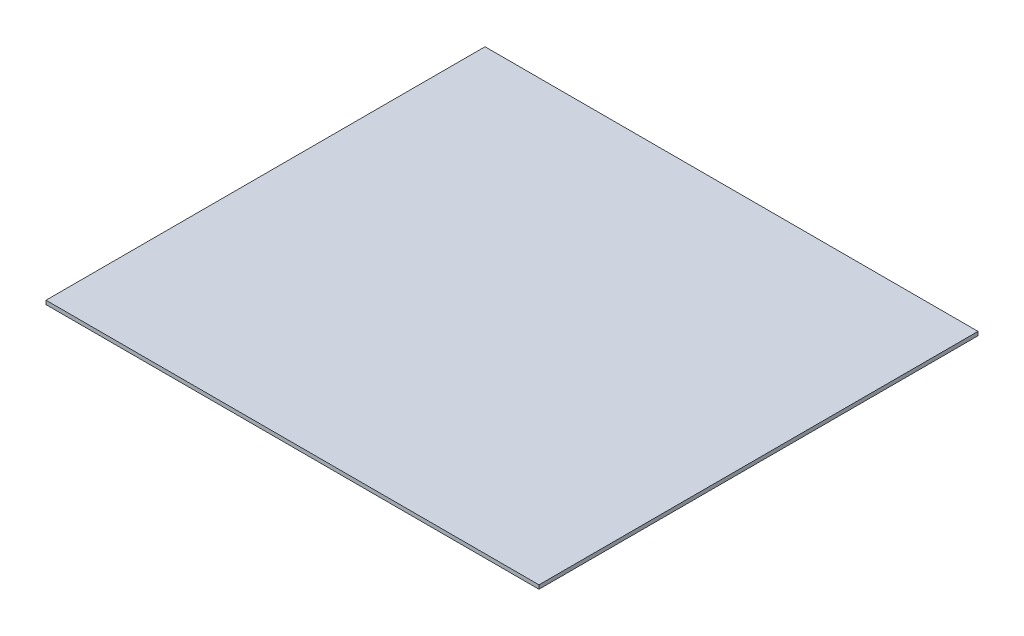
SolidWorks part; units mm, degrees
ref_plane "Front Plane" through (0, 0, 0) normal (0, 0, 1) x (1, 0, 0)
ref_plane "Top Plane" through (0, 0, 0) normal (0, 1, 0) x (1, 0, 0)
ref_plane "Right Plane" through (0, 0, 0) normal (1, 0, 0) x (0, 0, -1)
sketch "Sketch1" plane through (0, 0, 0) normal (0, 1, 0) x (1, 0, 0)
  line L1 (-64.175, -57.15) -> (64.175, -57.15)
  line L2 (-64.175, -57.15) -> (-64.175, 57.15)
  line L3 (-64.175, 57.15) -> (64.175, 57.15)
  line L4 (64.175, -57.15) -> (64.175, 57.15)
  line L5 (-64.175, -57.15) -> (64.175, 57.15) construction
  line L6 (-64.175, 57.15) -> (64.175, -57.15) construction
  point P0 (0, 0)
  dimension "D1" = 128.35
  dimension "D2" = 114.3
extrude "Boss-Extrude1" add sketch "Sketch1" along normal blind 1
